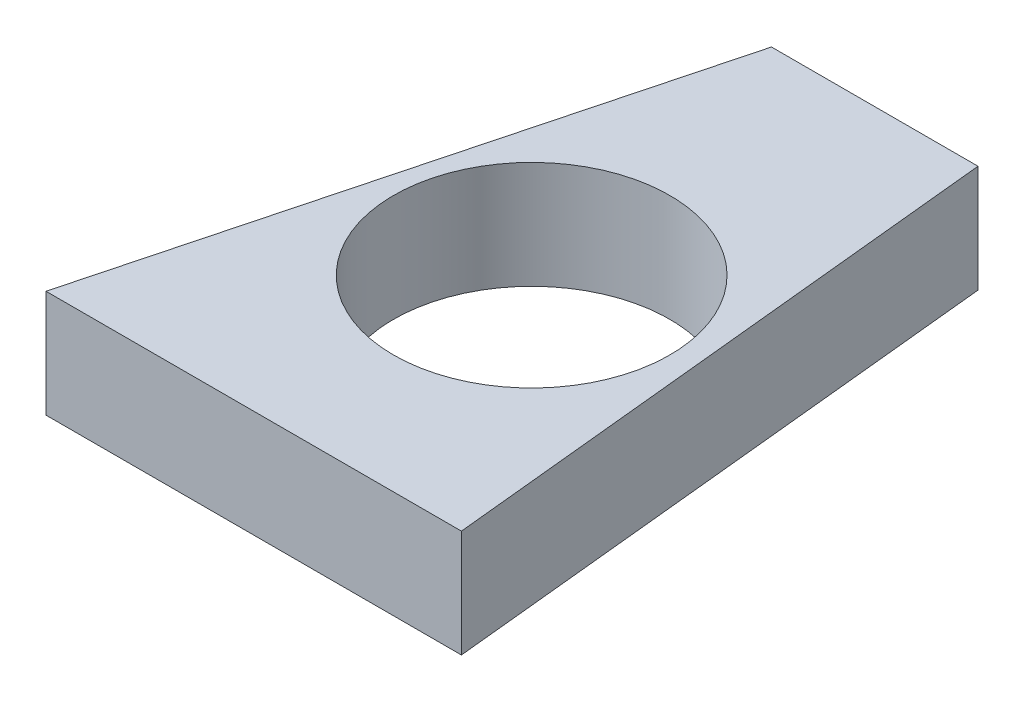
SolidWorks part; units mm, degrees
ref_plane "Front Plane" through (0, 0, 0) normal (0, 0, 1) x (1, 0, 0)
ref_plane "Top Plane" through (0, 0, 0) normal (0, 1, 0) x (1, 0, 0)
ref_plane "Right Plane" through (0, 0, 0) normal (1, 0, 0) x (0, 0, -1)
sketch "Sketch1" plane through (0, 0, 0) normal (0, 1, 0) x (1, 0, 0)
  line L0 (-77.8701, -87.3246) -> (63.4336, -87.3246)
  line L1 (63.4336, -87.3246) -> (43.804, 108.0147)
  line L2 (43.804, 108.0147) -> (-26.442, 108.0147)
  line L3 (-26.442, 108.0147) -> (-77.8701, -87.3246)
  circle A0 centre (0, 0) radius 47
  circle A2 centre (0, 0) radius 120.65
  point P10 (0, -47)
  point P11 (47, 0)
  point P16 (-47, 0)
  dimension "D2" = 94
  dimension "D3" = 7.62
  dimension "D4" = 7.62
  dimension "D1" = 241.3
extrude "Boss-Extrude1" add sketch "Sketch1" along normal blind 36.5 contours L2 L3 L0 L1 A0
